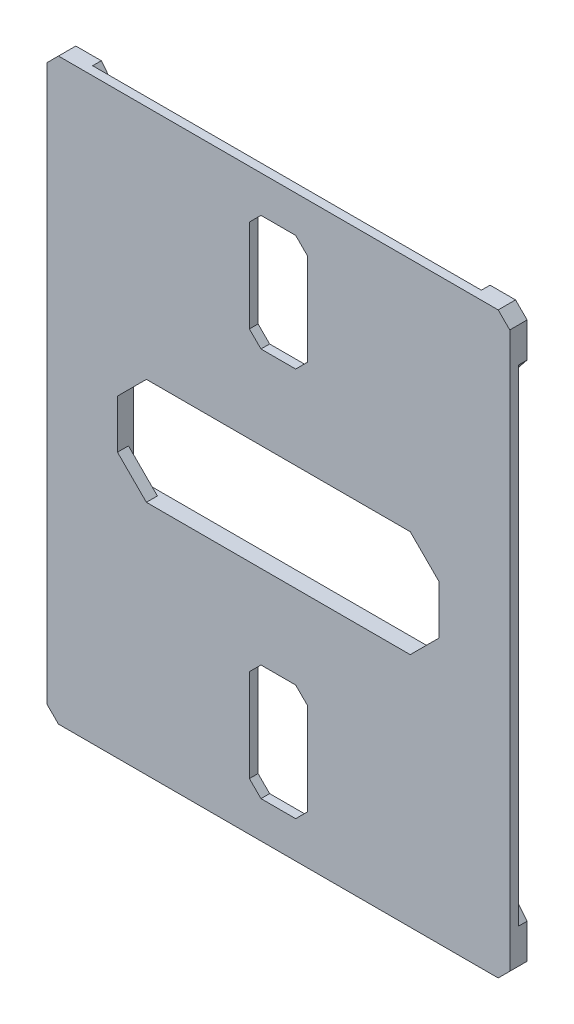
SolidWorks part; units mm, degrees
ref_plane "Plano frontal" through (0, 0, 0) normal (0, 0, 1) x (1, 0, 0)
ref_plane "Plano superior" through (0, 0, 0) normal (0, 1, 0) x (1, 0, 0)
ref_plane "Plano direito" through (0, 0, 0) normal (1, 0, 0) x (0, 0, -1)
sketch "Esboço1" plane through (0, 0, 0) normal (0, 0, 1) x (1, 0, 0)
  line L0 (27.6, -9) -> (27.6, 9) construction
  line L1 (27.6, 9) -> (-27.6, 9) construction
  line L2 (-27.6, 9) -> (-27.6, -9) construction
  line L3 (-27.6, -9) -> (27.6, -9) construction
sketch "Esboço2" plane through (0, 0, 0) normal (0, 0, 1) x (1, 0, 0)
  line L13 (-40, 50) -> (40, 50)
  line L14 (-40, 50) -> (-40, -50)
  line L15 (-40, -50) -> (40, -50)
  line L16 (40, 50) -> (40, -50)
  line L17 (0, 50) -> (0, -50) construction
  line L19 (-40, 0) -> (40, 0) construction
  line L28 (27.8, -9.2) -> (27.8, 9.2)
  line L29 (-27.8, -9.2) -> (27.8, -9.2)
  line L30 (-27.8, 9.2) -> (-27.8, -9.2)
  line L31 (27.8, 9.2) -> (-27.8, 9.2)
  line L32 (27.8, -9.2) -> (27.8, 9.2)
  line L33 (-27.8, -9.2) -> (27.8, -9.2)
  line L34 (-27.8, 9.2) -> (-27.8, -9.2)
  line L35 (27.8, 9.2) -> (-27.8, 9.2)
  dimension "D1" = 0.2
  dimension "D3" = 80
  dimension "D4" = 100
extrude "Ressalto-extrusão1" add sketch "Esboço2" along normal blind 0.8
sketch "Esboço3" plane through (0, 0, 0.8) normal (0, 0, 1) x (1, 0, 0)
  line L0 (-27.6, 0) -> (27.6, 0) construction
  line L3 (-27.6, 9) -> (-27.6, -9) construction
  line L5 (27.6, -9) -> (27.6, 9) construction
  line L8 (27.6, 9) -> (-27.6, 9) construction
  line L9 (0, 9) -> (0, -9) construction
  line L10 (-27.6, -9) -> (27.6, -9) construction
sketch "Esboço4" plane through (0, 0, 0) normal (0, 0, -1) x (-1, 0, 0)
  line L0 (5, 12.3) -> (3.4369, 12.3)
  line L6 (5, -12.3) -> (3.4369, -12.3)
  line L8 (-2.8104, 12.3) -> (-5, 12.3)
  line L13 (20.2431, -17.3) -> (35.9, -17.3)
  line L14 (5, -12.3) -> (3.4369, -12.3)
  line L20 (5, 12.3) -> (3.4369, 12.3)
  line L25 (-16.2431, 12.3) -> (-2.8104, 12.3)
  line L29 (-16.2431, -12.3) -> (-3.4369, -12.3)
  line L36 (3.4369, 12.3) -> (16.2431, 12.3)
  line L37 (-40, 41.9961) -> (-20.2431, 17.3)
  line L38 (-35.9, -17.3) -> (35.9, -17.3) construction
  line L43 (33.5969, 50) -> (7.4369, 17.3)
  line L44 (-33.5969, 50) -> (-7.4369, 17.3)
  line L46 (40, 41.9961) -> (20.2431, 17.3)
  line L47 (3.4369, -12.3) -> (16.2431, -12.3)
  line L50 (40, -50) -> (33.5969, -50)
  line L51 (40, -50) -> (40, -41.9961)
  line L53 (40, 50) -> (33.5969, 50)
  line L54 (-40, -50) -> (-40, -41.9961)
  line L55 (-3.4369, -12.3) -> (-5, -12.3)
  line L56 (-3.4369, -12.3) -> (-5, -12.3)
  line L58 (-33.5969, 50) -> (-40, 50)
  line L59 (-40, 41.9961) -> (-40, 50)
  line L60 (40, 41.9961) -> (40, 50)
  line L61 (-33.5969, -50) -> (-40, -50)
  line L62 (-30.9, 12.3) -> (30.9, 12.3)
  line L63 (-30.9, 12.3) -> (-30.9, -12.3)
  line L64 (-30.9, -12.3) -> (30.9, -12.3)
  line L65 (30.9, 12.3) -> (30.9, -12.3)
  line L68 (-7.4369, -17.3) -> (-33.5969, -50)
  line L69 (-20.2431, -17.3) -> (-40, -41.9961)
  line L70 (7.4369, -17.3) -> (33.5969, -50)
  line L71 (20.2431, -17.3) -> (40, -41.9961)
  line L72 (-35.9, -17.3) -> (-20.2431, -17.3)
  line L73 (35.9, 17.3) -> (35.9, -17.3)
  line L74 (-35.9, 17.3) -> (-20.2431, 17.3)
  line L75 (-35.9, 17.3) -> (-35.9, -17.3)
  line L80 (-7.4369, -17.3) -> (7.4369, -17.3)
  line L81 (-7.4369, 17.3) -> (7.4369, 17.3)
  line L82 (-35.9, 17.3) -> (35.9, 17.3) construction
  line L83 (20.2431, 17.3) -> (35.9, 17.3)
  line L84 (-27.6, -9) -> (-27.6, 9) construction
  line L85 (-27.6, 9) -> (27.6, 9) construction
  line L86 (27.6, 9) -> (27.6, -9) construction
  line L87 (27.6, -9) -> (-27.6, -9) construction
  point P0 (0, 0)
  point P6 (0, 0)
  point P8 (2.1896, 0)
  point P14 (2.1896, 0)
  point P16 (0, 0)
  line M11 (40, -50) -> (40, 50)
  line M12 (40, 50) -> (-40, 50)
  line M13 (-40, 50) -> (-40, -50)
  line M14 (-40, -50) -> (40, -50)
  dimension "D2" = 3.3
  dimension "D3" = 3.3
  dimension "D1" = 3.3
  dimension "D5" = 3.3
  dimension "D4" = 5
extrude "Ressalto-extrusão2" add sketch "Esboço4" along normal blind 2.2 contours L83 L46 L43 L81 L44 L37 L74 L75 L72 L69 L68 L80 L70 L71 L13 L73 L62 L65 L64 L47 L6 L29 L63 L25 L8 L0 L36 M11 M12 M13 M14
chamfer "Chanfro3" distance 5 angle 45 4 edges at (-35.9, 17.3, -1.1) (-35.9, -17.3, -1.1) (35.9, 17.3, -1.1) (35.9, -17.3, -1.1)
sketch "Esboço5" plane through (0, 0, 0) normal (0, 0, -1) x (-1, 0, 0)
  line L3 (-5, 43.65) -> (5, 43.65)
  line L4 (-5, 43.65) -> (-5, 23.65)
  line L5 (-5, 23.65) -> (5, 23.65)
  line L6 (5, 43.65) -> (5, 23.65)
  line L7 (-5, 43.65) -> (5, 23.65) construction
  line L8 (-5, 23.65) -> (5, 43.65) construction
  line L9 (-5, -43.65) -> (5, -43.65)
  line L10 (-5, -43.65) -> (-5, -23.65)
  line L11 (-5, -23.65) -> (5, -23.65)
  line L12 (5, -43.65) -> (5, -23.65)
  line L13 (-5, -43.65) -> (5, -23.65) construction
  line L14 (-5, -23.65) -> (5, -43.65) construction
  line L15 (-40, -41.9961) -> (-40, 41.9961) construction
  line L19 (33.5969, -50) -> (-33.5969, -50) construction
  line L20 (-33.5969, 50) -> (33.5969, 50) construction
  point P0 (0, 33.65)
  point P7 (0, -33.65)
  dimension "D1" = 10
  dimension "D2" = 10
  dimension "D3" = 40
  dimension "D4" = 40
  dimension "D5" = 16.35
  dimension "D6" = 16.35
  dimension "D7" = 20
  dimension "D8" = 20
extrude "Corte-extrusão1" cut sketch "Esboço5" against normal blind 10
chamfer "Chanfro4" distance 2 angle 45 8 edges at (5, -23.65, 0.4) (-5, -23.65, 0.4) (-5, -43.65, 0.4) (5, -43.65, 0.4) (5, 23.65, 0.4) (-5, 23.65, 0.4) (5, 43.65, 0.4) (-5, 43.65, 0.4)
chamfer "Chanfro5" distance 2 angle 45 4 edges at (40, 50, -0.7) (-40, 50, -0.7) (-40, -50, -0.7) (40, -50, -0.7)
sketch "Esboço6" plane through (0, 0, 0) normal (0, 0, -1) x (-1, 0, 0)
  line L0 (30.9, -17.3) -> (20.2431, -17.3) construction
  line L1 (20.2431, -17.3) -> (40, -41.9961) construction
  line L2 (40, -41.9961) -> (40, 41.9961) construction
  line L3 (40, 41.9961) -> (20.2431, 17.3) construction
  line L4 (20.2431, 17.3) -> (30.9, 17.3) construction
  line L5 (30.9, 17.3) -> (35.9, 12.3) construction
  line L6 (35.9, 12.3) -> (35.9, -12.3) construction
  line L7 (35.9, -12.3) -> (30.9, -17.3) construction
  line L8 (33.5969, 50) -> (-33.5969, 50) construction
  line L9 (-33.5969, 50) -> (-7.4369, 17.3) construction
  line L10 (-7.4369, 17.3) -> (7.4369, 17.3) construction
  line L11 (7.4369, 17.3) -> (33.5969, 50) construction
  line L12 (-40, -41.9961) -> (-20.2431, -17.3) construction
  line L13 (-20.2431, -17.3) -> (-30.9, -17.3) construction
  line L14 (-30.9, -17.3) -> (-35.9, -12.3) construction
  line L15 (-35.9, -12.3) -> (-35.9, 12.3) construction
  line L16 (-35.9, 12.3) -> (-30.9, 17.3) construction
  line L17 (-30.9, 17.3) -> (-20.2431, 17.3) construction
  line L18 (-20.2431, 17.3) -> (-40, 41.9961) construction
  line L19 (-40, 41.9961) -> (-40, -41.9961) construction
  line L20 (33.5969, -50) -> (7.4369, -17.3) construction
  line L21 (7.4369, -17.3) -> (-7.4369, -17.3) construction
  line L22 (-7.4369, -17.3) -> (-33.5969, -50) construction
  line L23 (-33.5969, -50) -> (33.5969, -50) construction
  line L24 (30.9, -17.3) -> (20.2431, -17.3)
  line L25 (20.2431, -17.3) -> (40, -41.9961)
  line L26 (40, -41.9961) -> (40, 41.9961)
  line L27 (40, 41.9961) -> (20.2431, 17.3)
  line L28 (20.2431, 17.3) -> (30.9, 17.3)
  line L29 (30.9, 17.3) -> (35.9, 12.3)
  line L30 (35.9, 12.3) -> (35.9, -12.3)
  line L31 (35.9, -12.3) -> (30.9, -17.3)
  line L32 (33.5969, 50) -> (-33.5969, 50)
  line L33 (-33.5969, 50) -> (-7.4369, 17.3)
  line L34 (-7.4369, 17.3) -> (7.4369, 17.3)
  line L35 (7.4369, 17.3) -> (33.5969, 50)
  line L36 (-40, -41.9961) -> (-20.2431, -17.3)
  line L37 (-20.2431, -17.3) -> (-30.9, -17.3)
  line L38 (-30.9, -17.3) -> (-35.9, -12.3)
  line L39 (-35.9, -12.3) -> (-35.9, 12.3)
  line L40 (-35.9, 12.3) -> (-30.9, 17.3)
  line L41 (-30.9, 17.3) -> (-20.2431, 17.3)
  line L42 (-20.2431, 17.3) -> (-40, 41.9961)
  line L43 (-40, 41.9961) -> (-40, -41.9961)
  line L44 (33.5969, -50) -> (7.4369, -17.3)
  line L45 (7.4369, -17.3) -> (-7.4369, -17.3)
  line L46 (-7.4369, -17.3) -> (-33.5969, -50)
  line L47 (-33.5969, -50) -> (33.5969, -50)
  line L48 (3, 43.65) -> (-3, 43.65) construction
  line L49 (-5, 41.65) -> (-3, 43.65) construction
  line L50 (-5, 41.65) -> (-5, 25.65) construction
  line L51 (-3, 23.65) -> (-5, 25.65) construction
  line L52 (-3, 23.65) -> (3, 23.65) construction
  line L53 (5, 25.65) -> (3, 23.65) construction
  line L54 (5, 25.65) -> (5, 41.65) construction
  line L55 (3, 43.65) -> (5, 41.65) construction
  line L56 (-5, -25.65) -> (-3, -23.65) construction
  line L57 (3, -23.65) -> (-3, -23.65) construction
  line L58 (3, -23.65) -> (5, -25.65) construction
  line L59 (5, -41.65) -> (5, -25.65) construction
  line L60 (5, -41.65) -> (3, -43.65) construction
  line L61 (-3, -43.65) -> (3, -43.65) construction
  line L62 (-3, -43.65) -> (-5, -41.65) construction
  line L63 (-5, -25.65) -> (-5, -41.65) construction
  line L64 (-5, -25.65) -> (-5, -41.65)
  line L65 (-3, -43.65) -> (-5, -41.65)
  line L66 (-3, -43.65) -> (3, -43.65)
  line L67 (5, -41.65) -> (3, -43.65)
  line L68 (5, -41.65) -> (5, -25.65)
  line L69 (3, -23.65) -> (5, -25.65)
  line L70 (3, -23.65) -> (-3, -23.65)
  line L71 (-5, -25.65) -> (-3, -23.65)
  line L72 (3, 43.65) -> (5, 41.65)
  line L73 (5, 25.65) -> (5, 41.65)
  line L74 (5, 25.65) -> (3, 23.65)
  line L75 (-3, 23.65) -> (3, 23.65)
  line L76 (-3, 23.65) -> (-5, 25.65)
  line L77 (-5, 41.65) -> (-5, 25.65)
  line L78 (-5, 41.65) -> (-3, 43.65)
  line L79 (3, 43.65) -> (-3, 43.65)
extrude "Ressalto-extrusão3" add sketch "Esboço6" along normal blind 0.7
sketch "Esboço7" plane through (0, 0, 0) normal (0, 0, -1) x (-1, 0, 0)
  line L1 (-30.9, 12.3) -> (30.9, 12.3)
  line L2 (-30.9, 12.3) -> (-30.9, -12.3)
  line L3 (-30.9, -12.3) -> (30.9, -12.3)
  line L4 (30.9, 12.3) -> (30.9, -12.3)
  line L5 (27.8, -9.2) -> (-27.8, -9.2)
  line L6 (27.8, -9.2) -> (27.8, 9.2)
  line L7 (27.8, 9.2) -> (-27.8, 9.2)
  line L8 (-27.8, -9.2) -> (-27.8, 9.2)
extrude "Ressalto-extrusão4" add sketch "Esboço7" along normal blind 2
sketch "Esboço8" plane through (0, 0, -2.2) normal (0, 0, -1) x (-1, 0, 0)
  line L1 (-30.9, 12.3) -> (30.9, 12.3)
  line L2 (-30.9, 12.3) -> (-30.9, -12.3)
  line L3 (-30.9, -12.3) -> (30.9, -12.3)
  line L4 (30.9, 12.3) -> (30.9, -12.3)
  line L32 (-33.5969, 50) -> (-38, 50)
  line L33 (-38, 50) -> (-40, 48)
  line L34 (-40, 48) -> (-40, 41.9961)
  line L35 (-40, 41.9961) -> (-20.2431, 17.3)
  line L36 (-20.2431, 17.3) -> (-30.9, 17.3)
  line L37 (-30.9, 17.3) -> (-35.9, 12.3)
  line L38 (-35.9, 12.3) -> (-35.9, -12.3)
  line L39 (-35.9, -12.3) -> (-30.9, -17.3)
  line L40 (-30.9, -17.3) -> (-20.2431, -17.3)
  line L41 (-20.2431, -17.3) -> (-40, -41.9961)
  line L42 (-40, -41.9961) -> (-40, -48)
  line L43 (-40, -48) -> (-38, -50)
  line L44 (-38, -50) -> (-33.5969, -50)
  line L45 (-33.5969, -50) -> (-7.4369, -17.3)
  line L46 (-7.4369, -17.3) -> (7.4369, -17.3)
  line L47 (7.4369, -17.3) -> (33.5969, -50)
  line L48 (33.5969, -50) -> (38, -50)
  line L49 (38, -50) -> (40, -48)
  line L50 (40, -48) -> (40, -41.9961)
  line L51 (40, -41.9961) -> (20.2431, -17.3)
  line L52 (20.2431, -17.3) -> (30.9, -17.3)
  line L53 (30.9, -17.3) -> (35.9, -12.3)
  line L54 (35.9, -12.3) -> (35.9, 12.3)
  line L55 (35.9, 12.3) -> (30.9, 17.3)
  line L56 (30.9, 17.3) -> (20.2431, 17.3)
  line L57 (20.2431, 17.3) -> (40, 41.9961)
  line L58 (40, 41.9961) -> (40, 48)
  line L59 (40, 48) -> (38, 50)
  line L60 (38, 50) -> (33.5969, 50)
  line L61 (33.5969, 50) -> (7.4369, 17.3)
  line L62 (7.4369, 17.3) -> (-7.4369, 17.3)
  line L63 (-7.4369, 17.3) -> (-33.5969, 50)
  line L68 (30.9, 17.3) -> (-30.9, 17.3)
  line L69 (-30.9, 17.3) -> (-35.9, 12.3)
  line L70 (-35.9, 12.3) -> (-35.9, -12.3)
  line L71 (-35.9, -12.3) -> (-30.9, -17.3)
  line L72 (-30.9, -17.3) -> (30.9, -17.3)
  line L85 (30.9, -17.3) -> (35.9, -12.3)
  line L86 (35.9, -12.3) -> (35.9, 12.3)
  line L87 (35.9, 12.3) -> (30.9, 17.3)
  dimension "D1" = 0
extrude "Ressalto-extrusão5" add sketch "Esboço8" along normal blind 0.6
sketch "Esboço9" plane through (0, 0, -2) normal (0, 0, -1) x (-1, 0, 0)
  line L0 (-27.6, 0) -> (27.6, 0) construction
  line L2 (0, 9) -> (0, -9) construction
chamfer "Chanfro6" distance 5 angle 45 4 edges at (-27.8, -9.2, -0.6) (-27.8, 9.2, -0.6) (27.8, 9.2, -0.6) (27.8, -9.2, -0.6)
sketch "Esboço11" plane through (0, 0, -2) normal (0, 0, -1) x (-1, 0, 0)
  line L1 (-27.8, 9.2) -> (27.8, 9.2)
  line L2 (-27.8, 9.2) -> (-27.8, -9.2)
  line L3 (-27.8, -9.2) -> (27.8, -9.2)
  line L4 (27.8, 9.2) -> (27.8, -9.2)
extrude "Corte-extrusão2" cut sketch "Esboço11" against normal blind 0.9
